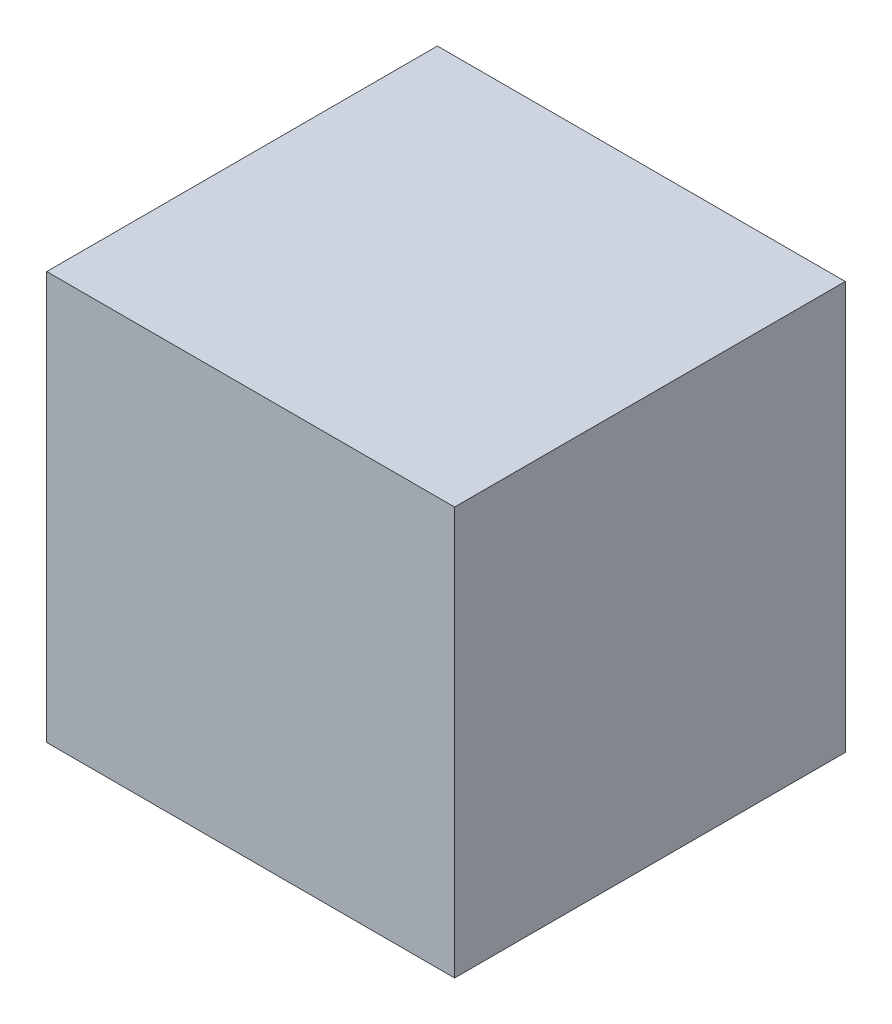
SolidWorks part; units mm, degrees
ref_plane "Front Plane" through (0, 0, 0) normal (0, 0, 1) x (1, 0, 0)
ref_plane "Top Plane" through (0, 0, 0) normal (0, 1, 0) x (1, 0, 0)
ref_plane "Right Plane" through (0, 0, 0) normal (1, 0, 0) x (0, 0, -1)
sketch "Sketch1" plane through (0, 0, 0) normal (0, 1, 0) x (1, 0, 0)
  line L1 (0, 0) -> (38, 0)
  line L2 (0, 0) -> (0, 36.4)
  line L3 (0, 36.4) -> (38, 36.4)
  line L4 (38, 0) -> (38, 36.4)
  point P5 (0, 0)
extrude "Boss-Extrude1" add sketch "Sketch1" along normal blind 38
